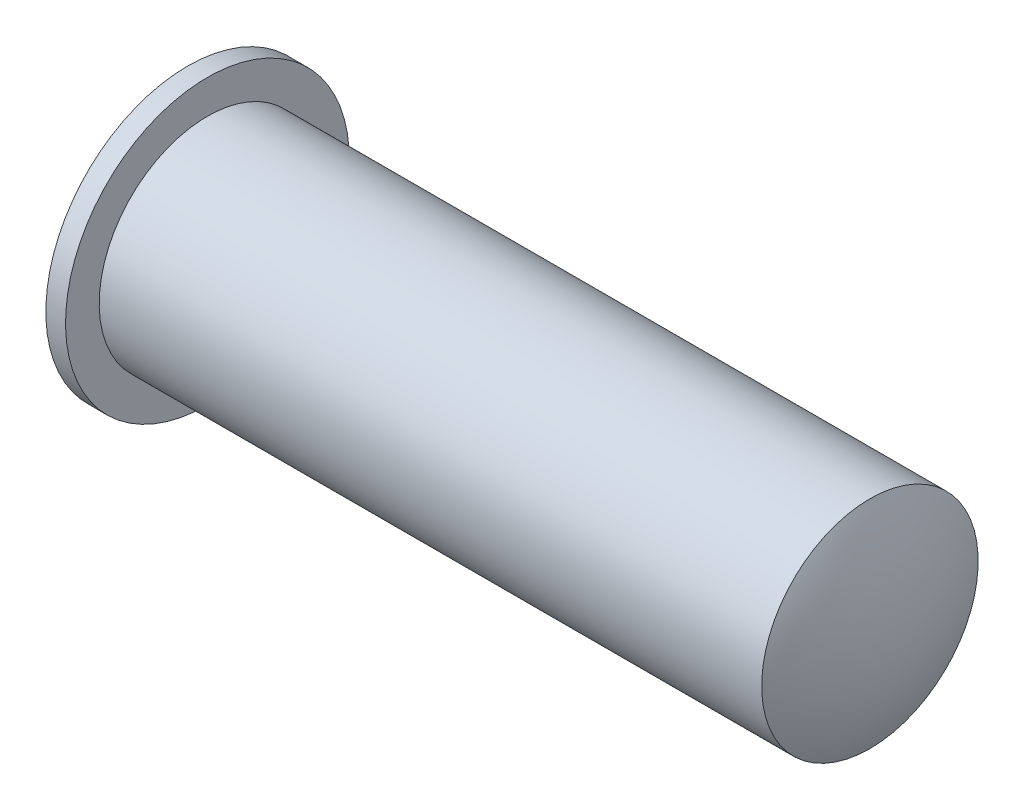
SolidWorks part; units mm, degrees
ref_plane "前视基准面" through (0, 0, 0) normal (0, 0, 1) x (1, 0, 0)
ref_plane "上视基准面" through (0, 0, 0) normal (0, 1, 0) x (1, 0, 0)
ref_plane "右视基准面" through (0, 0, 0) normal (1, 0, 0) x (0, 0, -1)
sketch "草图1" plane through (0, 0, 0) normal (0, 0, 1) x (1, 0, 0)
  line L0 (0, 7.2111) -> (1, 7.2111)
  line L1 (0, -55) -> (0, 55) construction
  line L2 (1, 7.2111) -> (1, 5.5)
  line L3 (1, 5.5) -> (34.6654, 5.5)
  line L4 (55, 0) -> (-55, 0) construction
  line L5 (-2, 0) -> (36, 0) construction
  line L6 (36, 0) -> (-2, 0)
  arc A0 (34.6654, 5.5) -> (36, 0) centre (24, 0) cw
  arc A1 (0, 7.2111) -> (-2, 0) centre (12, 0) ccw
  point P12 (0, 11.2326)
  point P13 (11.508, 0)
  point P14 (11.4725, 0)
  point P15 (13.209, 0)
  dimension "D1" = 14
  dimension "D2" = 12
  dimension "D3" = 1
  dimension "D4" = 3
  dimension "D5" = 38
  dimension "D6" = 11
  dimension "D7" = 14.4222
revolve "旋转1" add sketch "草图1" angle 360 about L5
